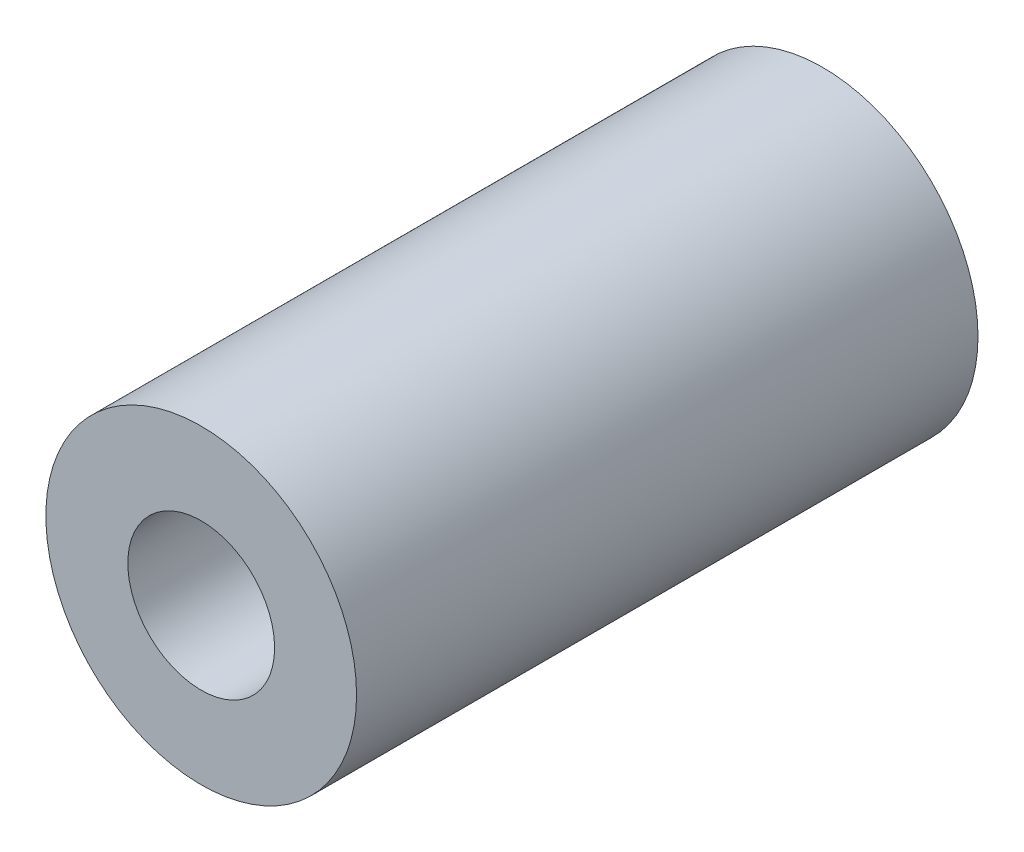
SolidWorks part; units mm, degrees
ref_plane "Front Plane" through (0, 0, 0) normal (0, 0, 1) x (1, 0, 0)
ref_plane "Top Plane" through (0, 0, 0) normal (0, 1, 0) x (1, 0, 0)
ref_plane "Right Plane" through (0, 0, 0) normal (1, 0, 0) x (0, 0, -1)
sketch "Sketch1" plane through (0, 0, 0) normal (0, 0, 1) x (1, 0, 0)
  circle A0 centre (0, 0) radius 2.25
  circle A1 centre (0, 0) radius 4.7625
  dimension "D1" = 4.5
  dimension "D2" = 9.525
extrude "Boss-Extrude1" add sketch "Sketch1" along normal blind 19.05
